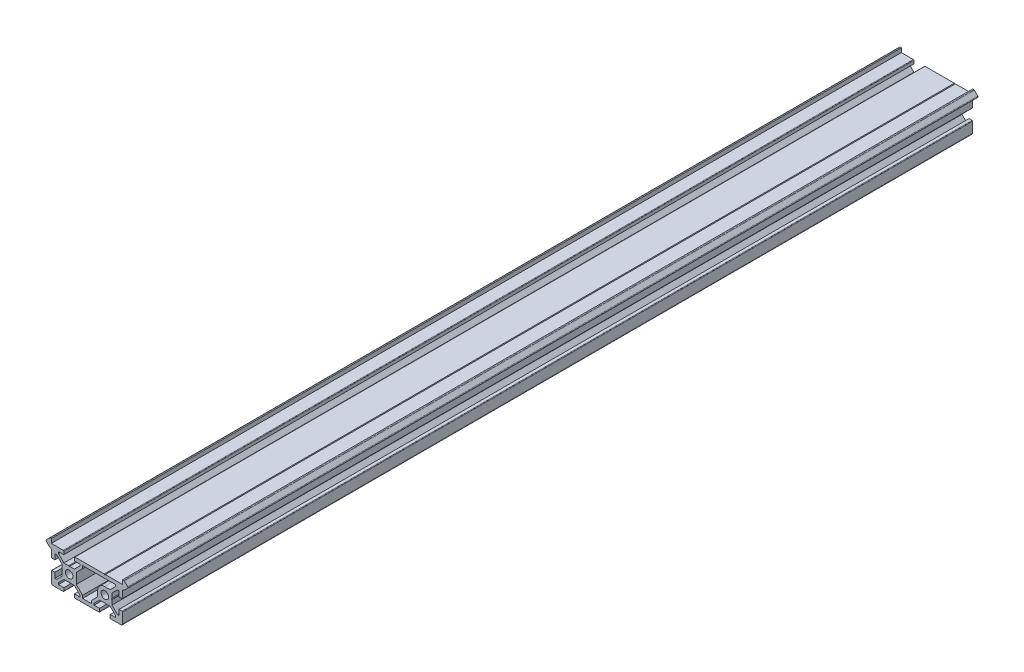
SolidWorks part; units mm, degrees
ref_plane "Front Plane" through (0, 0, 0) normal (0, 0, 1) x (1, 0, 0)
ref_plane "Top Plane" through (0, 0, 0) normal (0, 1, 0) x (1, 0, 0)
ref_plane "Right Plane" through (0, 0, 0) normal (1, 0, 0) x (0, 0, -1)
sketch "Model" plane through (0, 0, 0) normal (0, 0, 1) x (1, 0, 0)
  line L0 (0, 0) -> (0, 76.2) construction
  line L1 (0, 0) -> (101.6, 0) construction
  line L2 (0, 76.2) -> (101.6, 76.2) construction
  line L3 (101.6, 0) -> (101.6, 76.2) construction
  line L4 (28.7715, 48.1056) -> (30.6465, 49.9806)
  line L5 (31.5929, 50.127) -> (31.5929, 47.752)
  line L6 (31.5929, 44.877) -> (31.5929, 41.052)
  line L7 (31.5929, 34.452) -> (31.5929, 28.752)
  line L8 (33.5929, 31.752) -> (33.5929, 34.752)
  line L9 (33.5929, 40.752) -> (33.5929, 43.752)
  line L10 (35.5929, 29.752) -> (35.5929, 30.6914)
  line L11 (35.5929, 44.8127) -> (35.5929, 45.752)
  line L12 (37.5929, 40.6914) -> (37.5929, 38.052)
  line L13 (37.5929, 37.452) -> (37.5929, 34.8127)
  line L14 (38.5929, 28.052) -> (38.5929, 29.752)
  line L15 (38.5929, 45.752) -> (38.5929, 47.452)
  line L16 (32.5929, 27.752) -> (38.2929, 27.752)
  line L17 (44.8929, 27.752) -> (58.2929, 27.752)
  line L18 (64.8929, 27.752) -> (70.5929, 27.752)
  line L19 (37.5929, 38.052) -> (37.8929, 37.752)
  line L20 (41.5929, 34.052) -> (41.8929, 33.752)
  line L21 (30.6465, 45.5235) -> (28.7715, 47.3985)
  line L22 (41.8929, 41.752) -> (41.5929, 41.452)
  line L23 (37.8929, 37.752) -> (37.5929, 37.452)
  line L24 (67.5929, 29.752) -> (64.5929, 29.752)
  line L25 (58.5929, 29.752) -> (55.5929, 29.752)
  line L26 (54.0929, 29.752) -> (49.0929, 29.752)
  line L27 (47.5929, 29.752) -> (44.5929, 29.752)
  line L28 (38.5929, 29.752) -> (35.5929, 29.752)
  line L29 (34.5323, 43.752) -> (37.5929, 40.6914)
  line L30 (44.5323, 33.752) -> (47.5929, 30.6914)
  line L31 (44.5929, 47.452) -> (44.5929, 45.752)
  line L32 (44.5929, 29.752) -> (44.5929, 28.052)
  line L33 (47.5929, 44.8127) -> (44.5323, 41.752)
  line L34 (37.5929, 34.8127) -> (34.5323, 31.752)
  line L35 (69.5929, 31.752) -> (68.6536, 31.752)
  line L36 (34.5323, 31.752) -> (33.5929, 31.752)
  line L37 (49.0929, 31.3127) -> (45.5929, 34.8127)
  line L38 (38.6536, 41.752) -> (35.5929, 44.8127)
  line L39 (45.5929, 34.8127) -> (45.5929, 40.6914)
  line L40 (35.5929, 30.6914) -> (38.6536, 33.752)
  line L41 (45.5929, 40.6914) -> (49.0929, 44.1914)
  line L42 (38.6536, 33.752) -> (41.2929, 33.752)
  line L43 (41.8929, 33.752) -> (44.5323, 33.752)
  line L44 (58.6536, 33.752) -> (61.2929, 33.752)
  line L45 (61.8929, 33.752) -> (64.5323, 33.752)
  line L46 (41.5929, 41.452) -> (41.2929, 41.752)
  line L47 (47.5929, 45.752) -> (47.5929, 44.8127)
  line L48 (47.5929, 30.6914) -> (47.5929, 29.752)
  line L49 (41.2929, 33.752) -> (41.5929, 34.052)
  line L50 (71.2929, 34.752) -> (69.5929, 34.752)
  line L51 (33.5929, 34.752) -> (31.8929, 34.752)
  line L52 (49.0929, 29.752) -> (49.0929, 31.3127)
  line L53 (49.0929, 44.1914) -> (49.0929, 45.752)
  line L54 (61.5929, 47.452) -> (61.8929, 47.752)
  line L55 (31.8929, 40.752) -> (33.5929, 40.752)
  line L56 (69.5929, 40.752) -> (71.2929, 40.752)
  line L57 (54.0929, 31.3127) -> (54.0929, 29.752)
  line L58 (64.5323, 41.752) -> (61.4029, 41.752)
  line L59 (44.5323, 41.752) -> (41.8929, 41.752)
  line L60 (41.2929, 41.752) -> (38.6536, 41.752)
  line L61 (61.5929, 34.052) -> (61.8929, 33.752)
  line L62 (55.5929, 29.752) -> (55.5929, 30.6914)
  line L63 (33.5929, 43.752) -> (34.5323, 43.752)
  line L64 (68.6536, 43.752) -> (69.5929, 43.752)
  line L65 (57.5929, 37.942) -> (57.5929, 34.8127)
  line L66 (58.5929, 28.052) -> (58.5929, 29.752)
  line L67 (31.0929, 45.377) -> (31, 45.377)
  line L68 (72.0929, 45.377) -> (72.1858, 45.377)
  line L69 (35.5929, 45.752) -> (38.5929, 45.752)
  line L70 (44.5929, 45.752) -> (47.5929, 45.752)
  line L71 (49.0929, 45.752) -> (67.5929, 45.752)
  line L72 (64.5323, 33.752) -> (67.5929, 30.6914)
  line L73 (68.6536, 31.752) -> (65.5929, 34.8127)
  line L74 (67.5929, 44.8127) -> (64.5323, 41.752)
  line L75 (57.5929, 34.8127) -> (54.0929, 31.3127)
  line L76 (55.5929, 30.6914) -> (58.6536, 33.752)
  line L77 (65.5929, 40.6914) -> (68.6536, 43.752)
  line L78 (72.5394, 45.5235) -> (74.4144, 47.3985)
  line L79 (71.5929, 47.752) -> (61.8929, 47.752)
  line L80 (61.2929, 47.752) -> (44.8929, 47.752)
  line L81 (38.2929, 47.752) -> (31.5929, 47.752)
  line L82 (65.5929, 37.452) -> (65.2929, 37.752)
  line L83 (61.2929, 33.752) -> (61.5929, 34.052)
  line L84 (65.2929, 37.752) -> (65.5929, 38.052)
  line L85 (72.1858, 50.127) -> (71.5929, 50.127)
  line L86 (31, 50.127) -> (31.5929, 50.127)
  line L87 (64.5929, 29.752) -> (64.5929, 28.052)
  line L88 (61.2929, 47.752) -> (61.5929, 47.452)
  line L89 (65.5929, 34.8127) -> (65.5929, 37.452)
  line L90 (65.5929, 38.052) -> (65.5929, 40.6914)
  line L91 (67.5929, 45.752) -> (67.5929, 44.8127)
  line L92 (67.5929, 30.6914) -> (67.5929, 29.752)
  line L93 (69.5929, 43.752) -> (69.5929, 40.752)
  line L94 (69.5929, 34.752) -> (69.5929, 31.752)
  line L95 (71.5929, 50.127) -> (71.5929, 47.752)
  line L96 (71.5929, 28.752) -> (71.5929, 34.452)
  line L97 (71.5929, 41.052) -> (71.5929, 44.877)
  line L98 (74.4144, 48.1056) -> (72.5394, 49.9806)
  arc A0 (61.4029, 41.752) -> (57.5929, 37.942) centre (61.4029, 37.942) ccw
  circle A1 centre (61.5929, 37.752) radius 2.1
  circle A2 centre (41.5929, 37.752) radius 2.1
  arc A3 (31.5929, 28.752) -> (32.5929, 27.752) centre (32.5929, 28.752) ccw
  arc A4 (70.5929, 27.752) -> (71.5929, 28.752) centre (70.5929, 28.752) ccw
  arc A5 (31.5929, 44.877) -> (31.0929, 45.377) centre (31.0929, 44.877) ccw
  arc A6 (72.0929, 45.377) -> (71.5929, 44.877) centre (72.0929, 44.877) ccw
  arc A7 (31, 50.127) -> (30.6465, 49.9806) centre (31, 49.627) ccw
  arc A8 (28.7715, 48.1056) -> (28.7715, 47.3985) centre (29.125, 47.752) ccw
  arc A9 (30.6465, 45.5235) -> (31, 45.377) centre (31, 45.877) ccw
  arc A10 (72.5394, 49.9806) -> (72.1858, 50.127) centre (72.1858, 49.627) ccw
  arc A11 (74.4144, 47.3985) -> (74.4144, 48.1056) centre (74.0608, 47.752) ccw
  arc A12 (72.1858, 45.377) -> (72.5394, 45.5235) centre (72.1858, 45.877) ccw
  arc A13 (31.8929, 34.752) -> (31.5929, 34.452) centre (31.8929, 34.452) ccw
  arc A14 (44.8929, 47.752) -> (44.5929, 47.452) centre (44.8929, 47.452) ccw
  arc A15 (38.5929, 47.452) -> (38.2929, 47.752) centre (38.2929, 47.452) ccw
  arc A16 (31.5929, 41.052) -> (31.8929, 40.752) centre (31.8929, 41.052) ccw
  arc A17 (38.2929, 27.752) -> (38.5929, 28.052) centre (38.2929, 28.052) ccw
  arc A18 (44.5929, 28.052) -> (44.8929, 27.752) centre (44.8929, 28.052) ccw
  arc A19 (58.2929, 27.752) -> (58.5929, 28.052) centre (58.2929, 28.052) ccw
  arc A20 (64.5929, 28.052) -> (64.8929, 27.752) centre (64.8929, 28.052) ccw
  arc A21 (71.5929, 34.452) -> (71.2929, 34.752) centre (71.2929, 34.452) ccw
  arc A22 (71.2929, 40.752) -> (71.5929, 41.052) centre (71.2929, 41.052) ccw
extrude "Boss-Extrude1" add sketch "Model" along a picked direction on the side of the normal blind 476.36
ref_plane "Plane1" through (51.5929, 0, 0) normal (-1, 0, 0) x (0, 0, 1)
